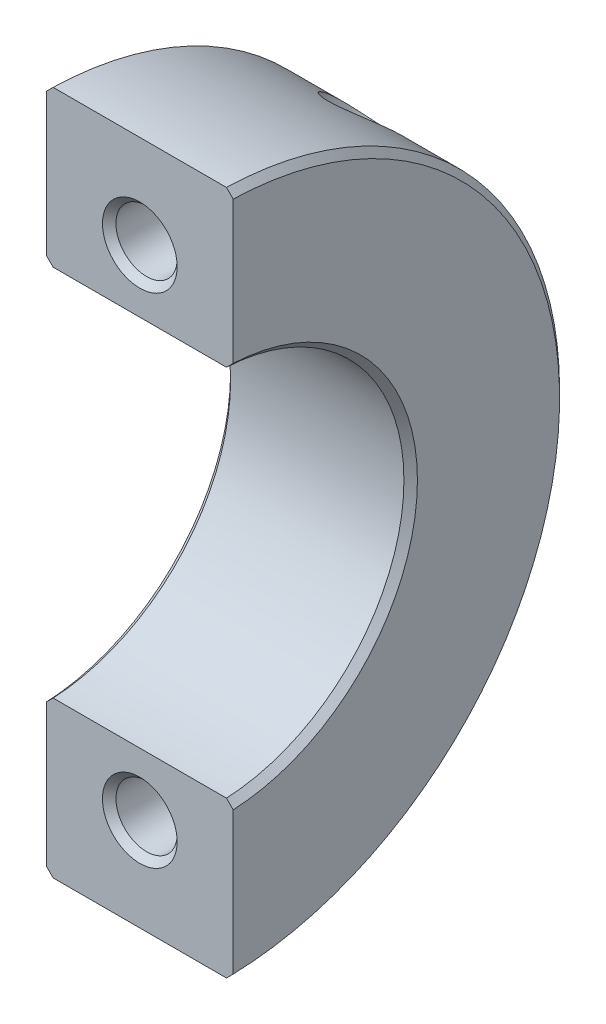
SolidWorks part; units mm, degrees
material "6061-O (SS)"
ref_plane "Front Plane" through (0, 0, 0) normal (0, 0, 1) x (1, 0, 0)
ref_plane "Top Plane" through (0, 0, 0) normal (0, 1, 0) x (1, 0, 0)
ref_plane "Right Plane" through (0, 0, 0) normal (1, 0, 0) x (0, 0, -1)
ref_plane "Plane1" through (7.5, 0, 0) normal (1, 0, 0) x (0, 0, -1)
sketch "Sketch1" plane through (7.5, 0, 0) normal (1, 0, 0) x (0, 0, -1)
  line L0 (0.75, 27.4898) -> (0.75, -27.4898)
  arc A0 (0.75, -27.4898) -> (0.75, 27.4898) centre (0, 0) ccw
extrude "Boss-Extrude1" add sketch "Sketch1" against normal blind 15
sketch "Sketch2" plane through (-7.5, 0, 0) normal (-1, 0, 0) x (0, 0, 1)
  line L0 (-0.75, -14.9812) -> (-0.75, 14.9812)
  arc A0 (-0.75, 14.9812) -> (-0.75, -14.9812) centre (0, 0) ccw
extrude "Cut-Extrude1" cut sketch "Sketch2" against normal through all
hole_wizard "Hole1" positions "Sketch4" profile "Sketch3" legacy
sketch "Sketch4" plane through (0, 0, -0.75) normal (0, 0, 1) x (1, 0, 0)
  point P0 (0, -20)
  point P1 (0, 20)
sketch "Sketch3" plane through (0, -20, -0.75) normal (1, 0, 0) x (0, -1, 0)
  line L0 (0, 0) -> (0, 26.75)
  line L1 (0, 26.75) -> (2.4585, 26.75)
  line L2 (2.4585, 26.75) -> (2.4585, 0)
  line L3 (2.4585, 0) -> (0, 0)
  line L4 (0, 110) -> (0, -10) construction
  dimension "Diameter" = 4.917
  dimension "Depth" = 26.75
chamfer "Chamfer1" distance 0.5415 angle 45 6 edges at (7.5, 0, -15) (2.4585, -20, -0.75) (-7.5, 0, -15) (7.5, 0, -27.5) (-7.5, 0, -27.5) (2.4585, 20, -0.75)
